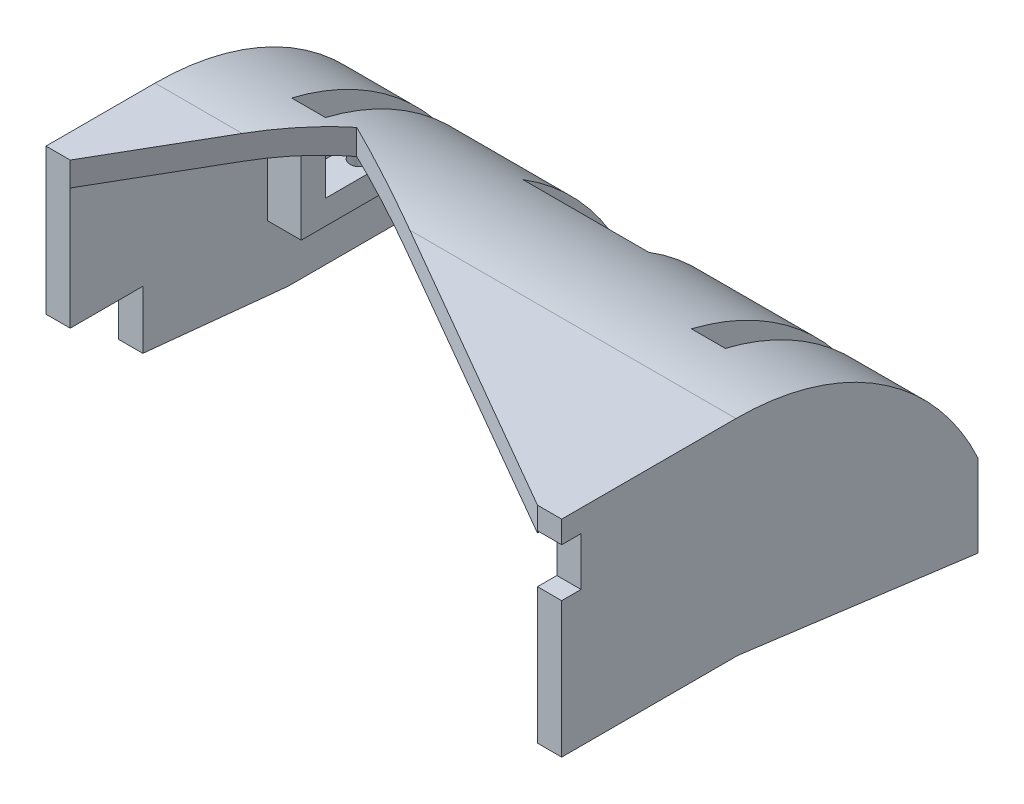
SolidWorks part; units mm, degrees
ref_plane "Front Plane" through (0, 0, 0) normal (0, 0, 1) x (1, 0, 0)
ref_plane "Top Plane" through (0, 0, 0) normal (0, 1, 0) x (1, 0, 0)
ref_plane "Right Plane" through (0, 0, 0) normal (1, 0, 0) x (0, 0, -1)
sketch "Sketch1" plane through (0, 0, 0) normal (1, 0, 0) x (0, 0, -1)
  line L0 (0, 55) -> (-36, 55)
  line L2 (50, 0) -> (50, -1)
  line L3 (50, -1) -> (55, -1)
  line L4 (55, -1) -> (55, 0)
  line L5 (-36, 55) -> (-36, 50)
  line L6 (-36, 50) -> (0, 50)
  arc A0 (50, 0) -> (0, 50) centre (0, 0) ccw
  arc A1 (55, 0) -> (0, 55) centre (0, 0) ccw
  dimension "D1" = 100
  dimension "D2" = 110
  dimension "D3" = 1
  dimension "D4" = 36
extrude "Boss-Extrude1" add sketch "Sketch1" along normal blind 110
sketch "Sketch2" plane through (0, 55, 0) normal (0, 1, 0) x (1, 0, 0)
  line L0 (110, 0) -> (110, -36) construction
  line L1 (99.8, 13) -> (92.8, 13)
  line L2 (99.8, 13) -> (99.8, 50)
  line L4 (92.8, 13) -> (92.8, 47)
  line L5 (110, 0) -> (0, 0) construction
  line L6 (55, -36) -> (55, 99.4915) construction
  line L7 (110, -36) -> (0, -36) construction
  line L8 (17.2, 13) -> (17.2, 47)
  line L10 (10.2, 13) -> (10.2, 50)
  line L11 (10.2, 13) -> (17.2, 13)
  line L12 (42, 47) -> (17.2, 47)
  line L13 (68, 29) -> (42, 29)
  line L14 (68, 29) -> (68, 47)
  line L16 (42, 29) -> (42, 47)
  line L17 (68, 47) -> (92.8, 47)
  line L18 (99.8, 50) -> (114.2239, 50)
  line L19 (114.2239, 50) -> (114.2239, 77.0757)
  line L20 (114.2239, 77.0757) -> (-27.8056, 77.0757)
  line L21 (-27.8056, 77.0757) -> (-27.8056, 50)
  line L22 (-27.8056, 50) -> (10.2, 50)
  dimension "D1" = 10.2
  dimension "D2" = 7
  dimension "D3" = 47
  dimension "D5" = 26
  dimension "D6" = 13
  dimension "D8" = 18
extrude "Cut-Extrude1" cut sketch "Sketch2" against normal blind 110
sketch "Sketch3" plane through (0, 0, -50) normal (0, 0, -1) x (-1, 0, 0)
  line L0 (0, 22.9129) -> (0, 0) construction
  line L1 (-110, 0) -> (0, 0)
  line L2 (-110, 0) -> (-110, 22.9129)
  line L3 (-110, 22.9129) -> (0, 22.9129)
  line L4 (0, 0) -> (0, 22.9129)
extrude "Cut-Extrude2" cut sketch "Sketch3" against normal blind 110
sketch "Sketch4" plane through (0, 22.9129, 0) normal (0, -1, 0) x (1, 0, 0)
  line L0 (42, -47) -> (17.2, -47) construction
  line L1 (110, -50) -> (99.8, -50)
  line L2 (110, -50) -> (110, -44.441)
  line L3 (110, -44.441) -> (99.8, -44.441)
  line L4 (99.8, -50) -> (99.8, -44.441)
  line L5 (92.8, -47) -> (68, -47)
  line L6 (92.8, -47) -> (92.8, -44.441)
  line L7 (92.8, -44.441) -> (68, -44.441)
  line L8 (68, -47) -> (68, -44.441)
  line L9 (42, -47) -> (17.2, -47)
  line L10 (42, -47) -> (42, -44.441)
  line L11 (42, -44.441) -> (17.2, -44.441)
  line L12 (17.2, -47) -> (17.2, -44.441)
  line L14 (10.2, -50) -> (0, -50)
  line L15 (10.2, -50) -> (10.2, -44.441)
  line L16 (10.2, -44.441) -> (0, -44.441)
  line L17 (0, -50) -> (0, -44.441)
extrude "Boss-Extrude2" add sketch "Sketch4" along normal blind 13
sketch "Sketch5" plane through (0, 50, 0) normal (0, -1, 0) x (1, 0, 0)
  line L0 (110, 0) -> (0, 0) construction
  line L1 (17.2, -13) -> (10.2, -13)
  line L2 (17.2, -13) -> (17.2, -8)
  line L3 (17.2, -8) -> (10.2, -8)
  line L4 (10.2, -13) -> (10.2, -8)
  line L5 (55, 0) -> (55, -70.981) construction
  line L6 (99.8, -13) -> (99.8, -8)
  line L7 (92.8, -8) -> (99.8, -8)
  line L8 (92.8, -13) -> (92.8, -8)
  line L9 (17.2, -13) -> (17.2, -47) construction
  line L10 (92.8, -13) -> (99.8, -13)
  dimension "D2" = 13
  dimension "D3" = 7
  dimension "D4" = 0
  dimension "D5" = 5
extrude "Boss-Extrude3" add sketch "Sketch5" along normal blind 16
sketch "Sketch6" plane through (0, 9.9129, 0) normal (0, -1, 0) x (1, 0, 0)
  line L1 (110, -44.441) -> (99.8, -44.441)
  line L2 (110, -44.441) -> (110, -50)
  line L3 (110, -50) -> (99.8, -50)
  line L4 (99.8, -44.441) -> (99.8, -50)
  line L5 (92.8, -44.441) -> (68, -44.441)
  line L6 (92.8, -44.441) -> (92.8, -47)
  line L7 (92.8, -47) -> (68, -47)
  line L8 (68, -44.441) -> (68, -47)
extrude "Boss-Extrude4" add sketch "Sketch6" along normal blind 4
sketch "Sketch7" plane through (0, 55, 0) normal (0, 1, 0) x (1, 0, 0)
  line L0 (110, -36) -> (21.6654, 15)
  line L1 (21.6654, 15) -> (0, -22.5256)
  line L2 (0, -36) -> (110, -36)
  line L3 (0, 0) -> (0, -36) construction
  line L4 (0, -22.5256) -> (0, -36)
  dimension "D2" = 51
  dimension "D3" = 30
  dimension "D4" = 90
extrude "Cut-Extrude3" cut sketch "Sketch7" against normal blind 64
sketch "Sketch8" plane through (0, 0, -13) normal (0, 0, -1) x (-1, 0, 0)
  line L0 (-17.2, 34) -> (-17.2, 48.2804) construction
  line L1 (-10.2, 34) -> (-17.2, 34)
  line L2 (-10.2, 34) -> (-10.2, 39)
  line L3 (-10.2, 39) -> (-17.2, 39)
  line L4 (-17.2, 34) -> (-17.2, 39)
  line L5 (-92.8, 34) -> (-92.8, 48.2804) construction
  line L6 (-92.8, 39) -> (-99.8, 39)
  line L7 (-92.8, 39) -> (-92.8, 34)
  line L8 (-92.8, 34) -> (-99.8, 34)
  line L9 (-99.8, 39) -> (-99.8, 34)
  dimension "D1" = 5
  dimension "D2" = 5
extrude "Boss-Extrude5" add sketch "Sketch8" along normal blind 15
sketch "Sketch9" plane through (0, 39, 0) normal (0, 1, 0) x (1, 0, 0)
  line L0 (10.2, 28) -> (17.2, 28) construction
  line L1 (92.8, 28) -> (99.8, 28) construction
  circle A0 centre (13.7, 23.6) radius 2
  circle A1 centre (96.3, 23.6) radius 2
  dimension "D1" = 4
  dimension "D2" = 4
  dimension "D3" = 4.4
  dimension "D4" = 4.4
extrude "Cut-Extrude4" cut sketch "Sketch9" against normal blind 10
sketch "Sketch10" plane through (0, 0, 0) normal (-1, 0, 0) x (0, 0, 1)
  line L0 (-50, 9.9129) -> (-22.4744, 9.9129)
  line L1 (22.5256, 24.9129) -> (22.5256, 55)
  line L2 (22.5256, 55) -> (0, 55)
  line L3 (-50, 9.9129) -> (-50, 22.9129)
  line L4 (22.5256, 24.9129) -> (7.5256, 24.9129)
  line L5 (7.5256, 24.9129) -> (7.5256, 12.9129)
  line L6 (7.5256, 12.9129) -> (-22.4744, 9.9129)
  arc A1 (0, 50) -> (-44.441, 22.9129) centre (0, 0) ccw construction
  arc A2 (0, 55) -> (-50, 22.9129) centre (0, 0) ccw
  dimension "D1" = 3
  dimension "D2" = 0
  dimension "D3" = 15
  dimension "D4" = 30
extrude "Boss-Extrude6" add sketch "Sketch10" along normal blind 5
sketch "Sketch11" plane through (110, 0, 0) normal (1, 0, 0) x (0, 0, -1)
  line L0 (-36, 50.4129) -> (-32, 50.4129)
  line L1 (-36, 12.4129) -> (-36, 40.4129)
  line L2 (-36, 55) -> (0, 55)
  line L3 (50, 5.9129) -> (50, 22.9129)
  line L4 (50, 5.9129) -> (0.4243, 12.4129)
  line L5 (0.4243, 12.4129) -> (-36, 12.4129)
  line L6 (-32, 50.4129) -> (-32, 40.4129)
  line L7 (-32, 40.4129) -> (-36, 40.4129)
  line L8 (-36, 50.4129) -> (-36, 55)
  arc A0 (50, 22.9129) -> (0, 55) centre (0, 0) ccw
  dimension "D1" = 6.5
  dimension "D2" = 50
  dimension "D3" = 28
  dimension "D4" = 10
  dimension "D5" = 4
extrude "Boss-Extrude7" add sketch "Sketch11" along normal blind 5
